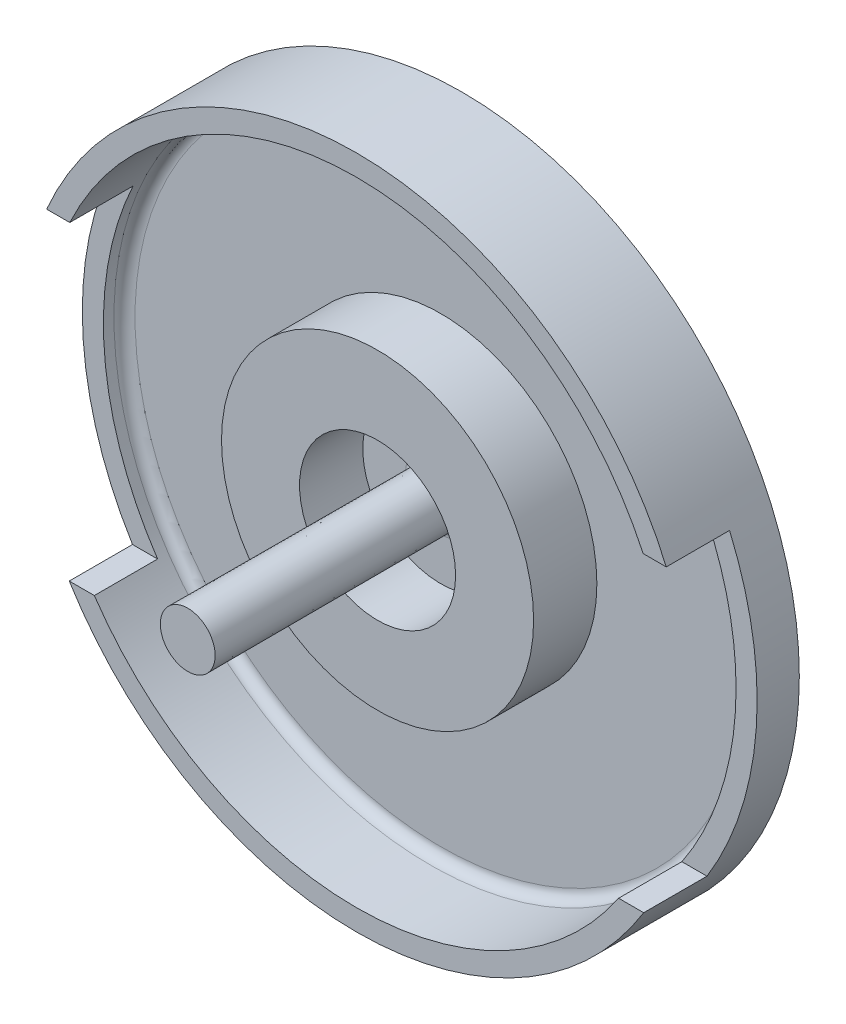
SolidWorks part; units mm, degrees
ref_plane "Front Plane" through (0, 0, 0) normal (0, 0, 1) x (1, 0, 0)
ref_plane "Top Plane" through (0, 0, 0) normal (0, 1, 0) x (1, 0, 0)
ref_plane "Right Plane" through (0, 0, 0) normal (1, 0, 0) x (0, 0, -1)
sketch "Sketch1" plane through (0, 0, 0) normal (0, 0, 1) x (1, 0, 0)
  circle A0 centre (0, 0) radius 16
extrude "Boss-Extrude1" add sketch "Sketch1" along normal blind 5
sketch "Sketch3" plane through (0, 0, 5) normal (0, 0, 1) x (1, 0, 0)
  circle A0 centre (0, 0) radius 15
extrude "Cut-Extrude1" cut sketch "Sketch3" against normal blind 4 contours A0
fillet "Fillet1" radius 0.5 1 edges at (15, 0, 1)
ref_plane "Plane4" through (0, 0, 13) normal (0, 0, 1) x (1, 0, 0)
sketch "Sketch7" plane through (0, 0, 13) normal (0, 0, 1) x (1, 0, 0)
  line L1 (-17.0905, 6.3393) -> (-11.822, 6.3393)
  line L2 (-17.0905, 6.3393) -> (-17.0905, -8.3958)
  line L3 (-17.0905, -8.3958) -> (-11.822, -8.3958)
  line L4 (-11.822, 6.3393) -> (-11.822, -8.3958)
  circle A0 centre (0, 0) radius 14.5 construction
extrude "Cut-Extrude2" cut sketch "Sketch7" against normal blind 11 contours L4 L3 L2 L1
mirror "Mirror1" about plane through (0, 0, 0) normal (1, 0, 0) of "Cut-Extrude2"
sketch "Sketch8" plane through (0, 0, 1) normal (0, 0, 1) x (1, 0, 0)
  circle A0 centre (0, 0) radius 7.4
extrude "Boss-Extrude2" add sketch "Sketch8" along normal blind 3 contours A0
sketch "Sketch9" plane through (0, 0, 4) normal (0, 0, 1) x (1, 0, 0)
  circle A0 centre (0, 0) radius 3.7
extrude "Cut-Extrude3" cut sketch "Sketch9" against normal blind 3
sketch "Sketch5" plane through (0, 0, 1) normal (0, 0, 1) x (1, 0, 0)
  circle A0 centre (0, 0) radius 1.275
  dimension "D1" = 2.55
sketch "Sketch6" plane through (0, 0, 13) normal (0, 0, 1) x (1, 0, 0)
  circle A0 centre (0, 0) radius 1.3
loft "Loft1" add profiles "Sketch5", "Sketch6"
fillet "Fillet3" radius 0.4 1 edges at (1.275, 0, 1)
